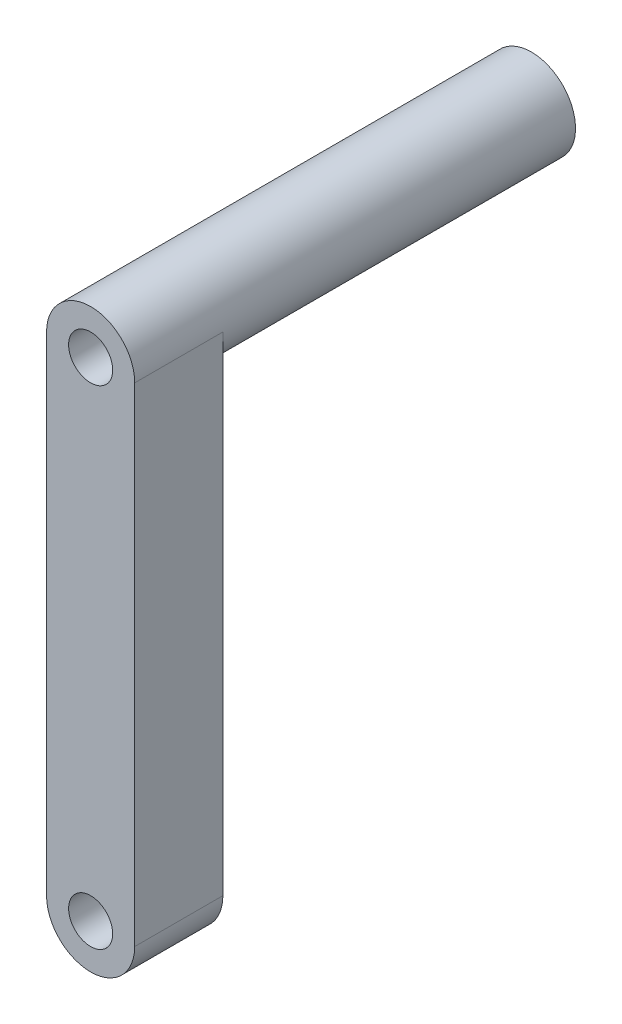
SolidWorks part; units mm, degrees
ref_plane "前视基准面" through (0, 0, 0) normal (0, 0, 1) x (1, 0, 0)
ref_plane "上视基准面" through (0, 0, 0) normal (0, 1, 0) x (1, 0, 0)
ref_plane "右视基准面" through (0, 0, 0) normal (1, 0, 0) x (0, 0, -1)
sketch "草图1" plane through (0, 0, 0) normal (0, 0, 1) x (1, 0, 0)
  line L2 (-1.0926, -5.0455) -> (-1.0926, 6.0294)
  line L4 (0.9074, -5.0455) -> (0.9074, 6.0294)
  arc A0 (0.9074, 6.0294) -> (-1.0926, 6.0294) centre (-0.0926, 6.0294) ccw
  arc A1 (-1.0926, -5.0455) -> (0.9074, -5.0455) centre (-0.0926, -5.0455) ccw
  circle A2 centre (-0.0926, -5.0455) radius 0.5
  circle A3 centre (-0.0926, 6.0294) radius 0.5
  point P0 (0, 0)
  dimension "D2" = 2
  dimension "D3" = 2
  dimension "D5" = 1
  dimension "D6" = 1
extrude "凸台-拉伸1" add sketch "草图1" along normal blind 2
sketch "草图3" plane through (0, 0, 0) normal (0, 0, -1) x (-1, 0, 0)
  circle A0 centre (0.0926, 6.0294) radius 0.5
  circle A1 centre (0.0926, 6.0294) radius 1
extrude "凸台-拉伸3" add sketch "草图3" along normal blind 8
